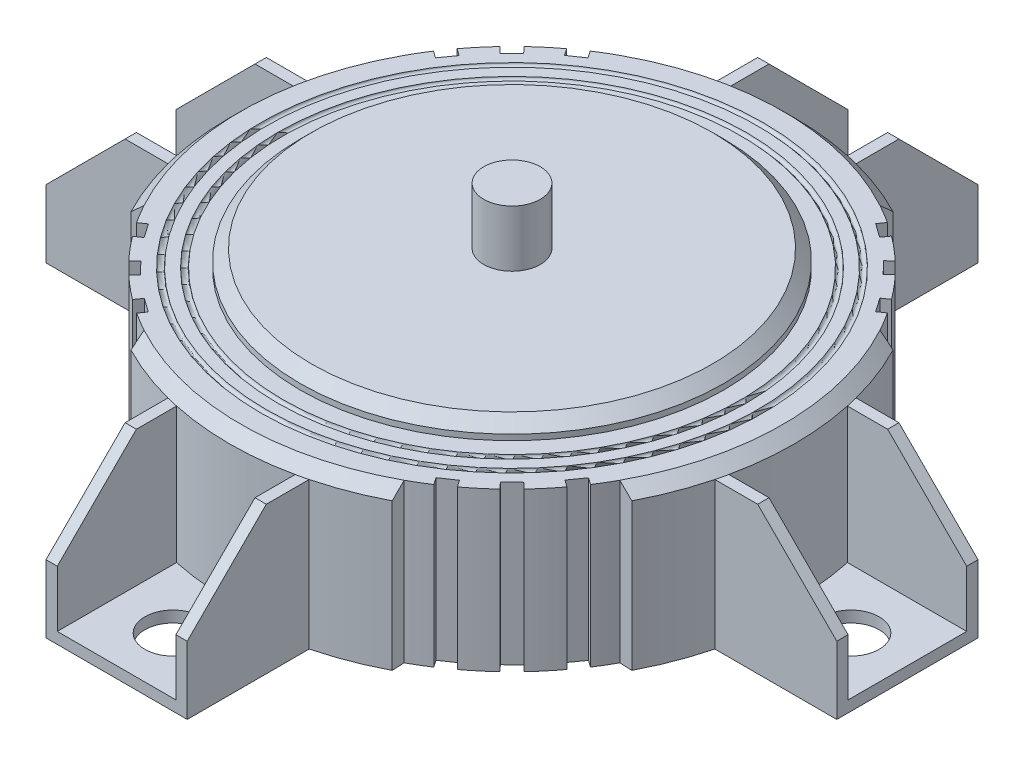
SolidWorks part; units mm, degrees
material "3.0205 (EN-AW 1200)"
ref_plane "Front Plane" through (0, 0, 0) normal (0, 0, 1) x (1, 0, 0)
ref_plane "Top Plane" through (0, 0, 0) normal (0, 1, 0) x (1, 0, 0)
ref_plane "Right Plane" through (0, 0, 0) normal (1, 0, 0) x (0, 0, -1)
sketch "Sketch1" plane through (0, 0, 0) normal (0, 0, 1) x (1, 0, 0)
  line L0 (0, 0) -> (0, 41) construction
  line L1 (0, 0) -> (-50, 0)
  line L2 (-50, 0) -> (-50, 28)
  line L3 (-50, 28) -> (-37.5, 28)
  line L4 (-37.5, 28) -> (-37.5, 31)
  line L5 (-37.5, 31) -> (-5, 31)
  line L6 (-5, 31) -> (-5, 41)
  line L7 (-5, 41) -> (0, 41)
  line L8 (0, 0) -> (0, 41)
  dimension "D2" = 100
  dimension "D3" = 75
  dimension "D4" = 10
  dimension "D5" = 3
  dimension "D6" = 28
revolve "Revolve1" add sketch "Sketch1" angle 360 about L0
chamfer "Chamfer1" distance 2 angle 45 2 edges at (0, 28, -50) (0, 31, -37.5)
sketch "Sketch3" plane through (0, 0, 0) normal (0, 0, 1) x (1, 0, 0)
  line L0 (0, 0) -> (0, 26) construction
  line L1 (-50, 0) -> (50, 0) construction
  line L2 (50, 26) -> (-50, 26) construction
  line L3 (-12.5, 26) -> (-12.5, 0)
  line L4 (-12.5, 0) -> (12.5, 0)
  line L5 (0, 0) -> (0, 2)
  line L6 (10.5, 2) -> (-10.5, 2)
  line L7 (-10.5, 2) -> (-10.5, 26)
  line L8 (-10.5, 26) -> (-12.5, 26)
  line L9 (12.5, 26) -> (12.5, 0)
  line L10 (10.5, 2) -> (10.5, 26)
  line L11 (10.5, 26) -> (12.5, 26)
  dimension "D1" = 2
  dimension "D2" = 2
  dimension "D3" = 25
extrude "Boss-Extrude1" add sketch "Sketch3" along normal blind 70 contours L6 L7 L8 L3 L4 L9 L11 L10
chamfer "Chamfer3" distance 14 2 edges at (11.5, 26, 70) (-11.5, 26, 70)
sketch "Sketch7" plane through (0, 0, 0) normal (0, 1, 0) x (1, 0, 0)
  line L0 (0, 0) -> (0, -60) construction
  circle A0 centre (0, -60) radius 5
  point P6 (0, -57.15)
  point P7 (0, 0)
  dimension "D1" = 60
extrude "Cut-Extrude1" cut sketch "Sketch7" along normal blind 70 contours A0
pattern_circular "CirPattern4" count 4 over 360 about axis through (0, 0, 0) along (0, 1, 0) of "Cut-Extrude1", "Chamfer3", "Boss-Extrude1"
sketch "Sketch12" plane through (0, 0, 0) normal (0, 1, 0) x (1, 0, 0)
  line L0 (23.0251, -42.117) -> (23.1202, -44.3334)
  line L1 (42.117, -23.0251) -> (44.3334, -23.1202)
  line L2 (0, 0) -> (51.1953, -51.1953) construction
  arc A0 (44.3334, -23.1202) -> (23.1202, -44.3334) centre (0, 0) cw
  arc A1 (12.5, -48.4123) -> (48.4123, -12.5) centre (0, 0) ccw construction
  arc A2 (42.117, -23.0251) -> (23.0251, -42.117) centre (0, 0) cw
  circle A3 centre (0, 0) radius 48 construction
  point P11 (33.9411, -33.9411)
  point P12 (35.3553, -35.3553)
  dimension "D1" = 30
  dimension "D2" = 27
extrude "Cut-Extrude3" cut sketch "Sketch12" along normal blind 70
sketch "Sketch19" plane through (0, 0, 0) normal (0, 1, 0) x (1, 0, 0)
  line L0 (0, 0) -> (47.8575, -47.8575) construction
  line L1 (38.3966, -29.4857) -> (44.3495, -23.5327) construction
  line L6 (44.3495, -23.5327) -> (38.3966, -29.4857) construction
  line L9 (36.0623, -33.9411) -> (33.9178, -36.0389)
  line L10 (33.9178, -36.0389) -> (31.8199, -33.8944)
  line L11 (31.8199, -33.8944) -> (33.9645, -31.7966)
  line L13 (36.0623, -33.9411) -> (33.9645, -31.7966)
  line L14 (33.9411, -33.9411) -> (25.3263, -42.556) construction
  arc A1 (23.0251, -42.117) -> (42.117, -23.0251) centre (0, 0) ccw construction
  point P3 (33.9411, -33.9411)
  point P9 (34.99, -34.99)
  point P15 (35.0134, -32.8688)
  point P16 (0, 0)
  dimension "D1" = 3
  dimension "D2" = 3
extrude "Cut-Extrude4" cut sketch "Sketch19" along normal blind 70 contours L13 L11 L10 L9
pattern_circular "CirPattern5" count 2 every 10 about axis through (0, 0, 0) along (0, 1, 0) of "Cut-Extrude4"
pattern_circular "CirPattern7" count 4 over 360 about axis through (0, 0, 0) along (0, 1, 0) of "Cut-Extrude4", "Cut-Extrude3", "CirPattern5"
sketch "Sketch27" plane through (0, 28, 0) normal (0, 1, 0) x (1, 0, 0)
  circle A0 centre (0, 0) radius 41
  circle A1 centre (0, 0) radius 44
sweep "Cut-Sweep2" cut path "Sketch27" circular profile diameter 1 parameters "D3"=1
sketch "Sketch102" plane through (0, 28, 0) normal (0, 1, 0) x (1, 0, 0)
  circle A0 centre (0, 0) radius 44
sweep "Cut-Sweep9" cut path "Sketch102" circular profile diameter 1 parameters "D3"=1
sketch "Sketch109" plane through (0, 0, 0) normal (0, -1, 0) x (-1, 0, 0)
  circle A0 centre (0, 0) radius 37.5
extrude "Cut-Extrude5" cut sketch "Sketch109" against normal blind 10
